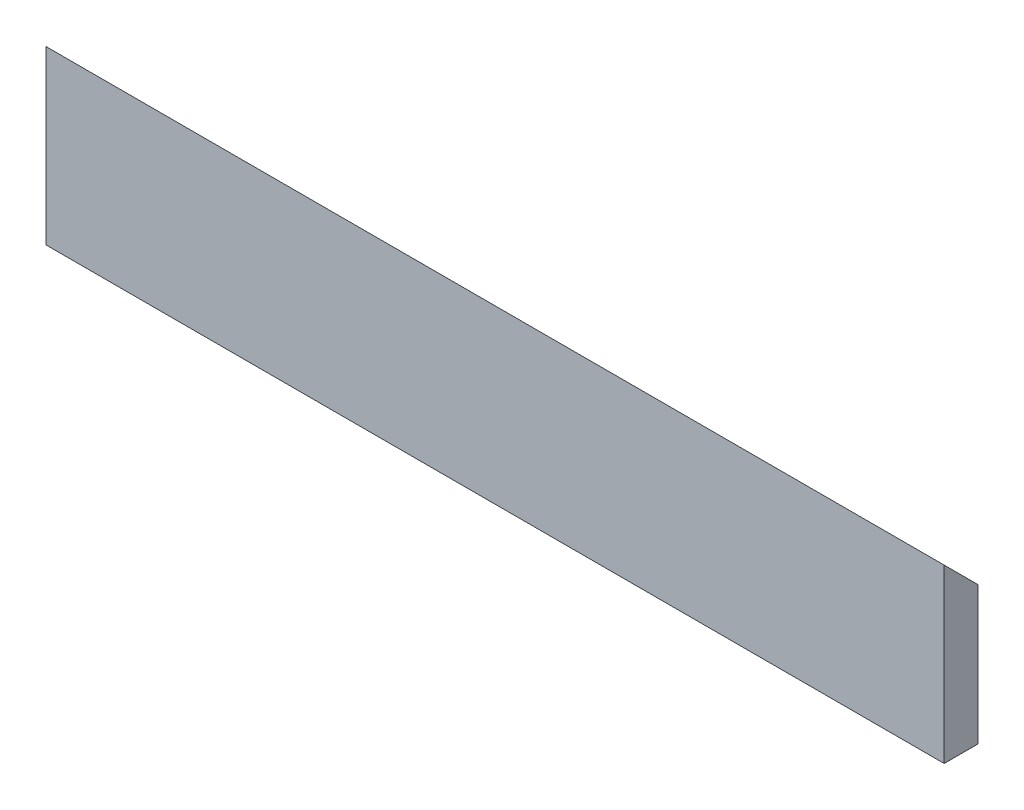
SolidWorks part; units mm, degrees
material "轻木"
ref_plane "Front" through (0, 0, 0) normal (0, 0, 1) x (1, 0, 0)
ref_plane "Top" through (0, 0, 0) normal (0, 1, 0) x (1, 0, 0)
ref_plane "Right" through (0, 0, 0) normal (1, 0, 0) x (0, 0, -1)
sketch "草图1" plane through (0, 0, 0) normal (0, 0, 1) x (1, 0, 0)
  line L1 (0, 0) -> (322.1, 0)
  line L2 (0, 0) -> (0, 76.2)
  line L3 (0, 76.2) -> (322.1, 76.2)
  line L5 (322.1, 76.2) -> (398.3, 76.2)
  line L6 (322.1, 76.2) -> (322.1, 0) construction
  line L7 (322.1, 0) -> (398.3, 0)
  line L8 (398.3, 76.2) -> (398.3, 0)
  dimension "D1" = 322.1
  dimension "D2" = 76.2
  dimension "D3" = 76.2
extrude "凸台-拉伸1" add sketch "草图1" along normal blind 15
sketch "草图6" plane through (0, 0, 0) normal (0, 1, 0) x (1, 0, 0)
  line L0 (322.1, 78.2684) -> (322.1, 27.4735) construction
  line L1 (398.3, -15) -> (398.3, 0) construction
  line L2 (157.5149, 40.3804) -> (157.5149, -41.849) construction
  line L3 (22.2006, -7.5) -> (121.9168, -7.5) construction
  line L4 (398.3, 0) -> (0, 0) construction
  line L5 (398.3, -15) -> (0, -15) construction
  line L6 (0, -7.5) -> (0, 40.5886) construction
  circle A0 centre (157.5149, -7.5) radius 1
  circle A1 centre (195.6149, -7.5) radius 1
  circle A2 centre (233.7149, -7.5) radius 1
  circle A3 centre (271.8149, -7.5) radius 1
  circle A4 centre (119.4149, -7.5) radius 1
  circle A5 centre (81.3149, -7.5) radius 1
  circle A6 centre (43.2149, -7.5) radius 1
  dimension "D3" = 2
  dimension "D1" = 76.2
  dimension "D2" = 164.5851
  dimension "D4" = 4
  dimension "D5" = 4
extrude "切除-拉伸1" cut sketch "草图6" against normal blind 50.8 from surface at 76.2 starting at face at (199.15, 76.2, 7.5)
sketch "草图3" plane through (0, 0, 0) normal (-1, 0, 0) x (0, 0, 1)
  line L0 (0, 76.2) -> (15, 76.2)
  line L1 (15, 76.2) -> (0, 61.2)
  line L2 (0, 76.2) -> (0, 0) construction
  line L3 (0, 61.2) -> (0, 76.2)
  dimension "D1" = 15
extrude "切除-拉伸2" cut sketch "草图3" against normal through all
equation "\"in\"=0.1"
